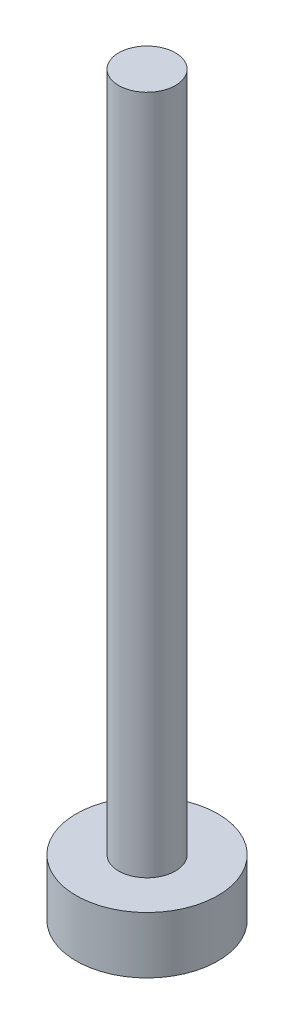
SolidWorks part; units mm, degrees
ref_plane "Front Plane" through (0, 0, 0) normal (0, 0, 1) x (1, 0, 0)
ref_plane "Top Plane" through (0, 0, 0) normal (0, 1, 0) x (1, 0, 0)
ref_plane "Right Plane" through (0, 0, 0) normal (1, 0, 0) x (0, 0, -1)
sketch "Sketch1" plane through (0, 0, 0) normal (0, 1, 0) x (1, 0, 0)
  circle A0 centre (0, 0) radius 1
  dimension "D1" = 2
extrude "Boss-Extrude1" add sketch "Sketch1" along normal blind 24
sketch "Sketch2" plane through (0, 0, 0) normal (0, -1, 0) x (1, 0, 0)
  circle A0 centre (0, 0) radius 2.5
  dimension "D1" = 5
extrude "Boss-Extrude2" add sketch "Sketch2" along normal blind 2
sketch "Sketch3" plane through (0, -2, 0) normal (0, -1, 0) x (1, 0, 0)
  line L1 (-0.5, -2.15) -> (0.5, -2.15)
  line L2 (-0.5, -2.15) -> (-0.5, 2.15)
  line L3 (-0.5, 2.15) -> (0.5, 2.15)
  line L4 (0.5, -2.15) -> (0.5, 2.15)
  line L5 (-0.5, -2.15) -> (0.5, 2.15) construction
  line L6 (-0.5, 2.15) -> (0.5, -2.15) construction
  line L7 (-2.15, -0.5) -> (2.15, -0.5)
  line L8 (-2.15, -0.5) -> (-2.15, 0.5)
  line L9 (-2.15, 0.5) -> (2.15, 0.5)
  line L10 (2.15, -0.5) -> (2.15, 0.5)
  line L11 (-2.15, -0.5) -> (2.15, 0.5) construction
  line L12 (-2.15, 0.5) -> (2.15, -0.5) construction
  point P0 (0, 0)
  point P6 (0, 0)
  dimension "D1" = 1
  dimension "D2" = 4.3
extrude "Cut-Extrude1" cut sketch "Sketch3" against normal blind 0.5 contours L7 L10 L9 L4 | L7 L2 L1 L4 | L9 L8 L7 L2 | L2 L9 L4 L3 | L9 L2 L7 L4
fillet "Fillet1" radius 0.2 12 edges at (0.5, -1.5, -1.325) (0, -1.5, -2.15) (-0.5, -1.5, -1.325) (-1.325, -1.5, -0.5) (-2.15, -1.5, 0) (-1.325, -1.5, 0.5) (-0.5, -1.5, 1.325) (0, -1.5, 2.15) (0.5, -1.5, 1.325) (1.325, -1.5, 0.5) (2.15, -1.5, 0) (1.325, -1.5, -0.5)
